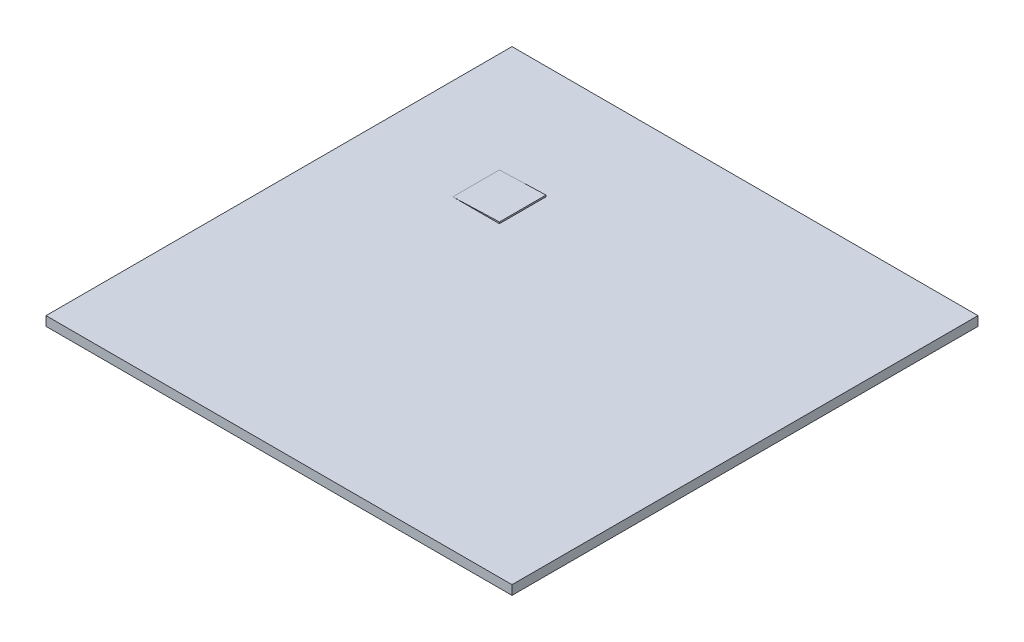
SolidWorks part; units mm, degrees
ref_plane "Front Plane" through (0, 0, 0) normal (0, 0, 1) x (1, 0, 0)
ref_plane "Top Plane" through (0, 0, 0) normal (0, 1, 0) x (1, 0, 0)
ref_plane "Right Plane" through (0, 0, 0) normal (1, 0, 0) x (0, 0, -1)
sketch "Sketch1" plane through (0, 0, 0) normal (0, 1, 0) x (1, 0, 0)
  line L1 (-2500, -2500) -> (2500, -2500)
  line L2 (-2500, -2500) -> (-2500, 2500)
  line L3 (-2500, 2500) -> (2500, 2500)
  line L4 (2500, -2500) -> (2500, 2500)
  line L5 (-2500, -2500) -> (2500, 2500) construction
  line L6 (-2500, 2500) -> (2500, -2500) construction
  point P0 (0, 0)
  dimension "D1" = 5000
  dimension "D2" = 5000
extrude "Boss-Extrude1" add sketch "Sketch1" along normal blind 100
sketch "Sketch2" plane through (0, 100, 0) normal (0, 1, 0) x (1, 0, 0)
  line L1 (-1421.4079, 1286.3836) -> (-921.4079, 1286.3836)
  line L2 (-1421.4079, 1286.3836) -> (-1421.4079, 786.3836)
  line L3 (-1421.4079, 786.3836) -> (-921.4079, 786.3836)
  line L4 (-921.4079, 1286.3836) -> (-921.4079, 786.3836)
  line L5 (-1421.4079, 1286.3836) -> (-921.4079, 786.3836) construction
  line L6 (-1421.4079, 786.3836) -> (-921.4079, 1286.3836) construction
  point P0 (-1171.4079, 1036.3836)
  dimension "D1" = 500
  dimension "D2" = 500
extrude "Boss-Extrude2" add sketch "Sketch2" along normal blind 50
sketch "Sketch3" plane through (0, 0, -786.3836) normal (0, 0, 1) x (1, 0, 0)
  line L0 (-1421.4079, 100) -> (-921.4079, 116.2726)
  line L1 (-921.4079, 150) -> (-921.4079, 100) construction
  line L2 (-921.4079, 116.2726) -> (-921.4079, 150)
  line L3 (-921.4079, 150) -> (-1421.4079, 150)
  line L4 (-1421.4079, 150) -> (-1421.4079, 100)
extrude "Cut-Extrude1" cut sketch "Sketch3" against normal up to surface (500 mm away) up to face at (-1171.4079, 125, -1286.3836)
